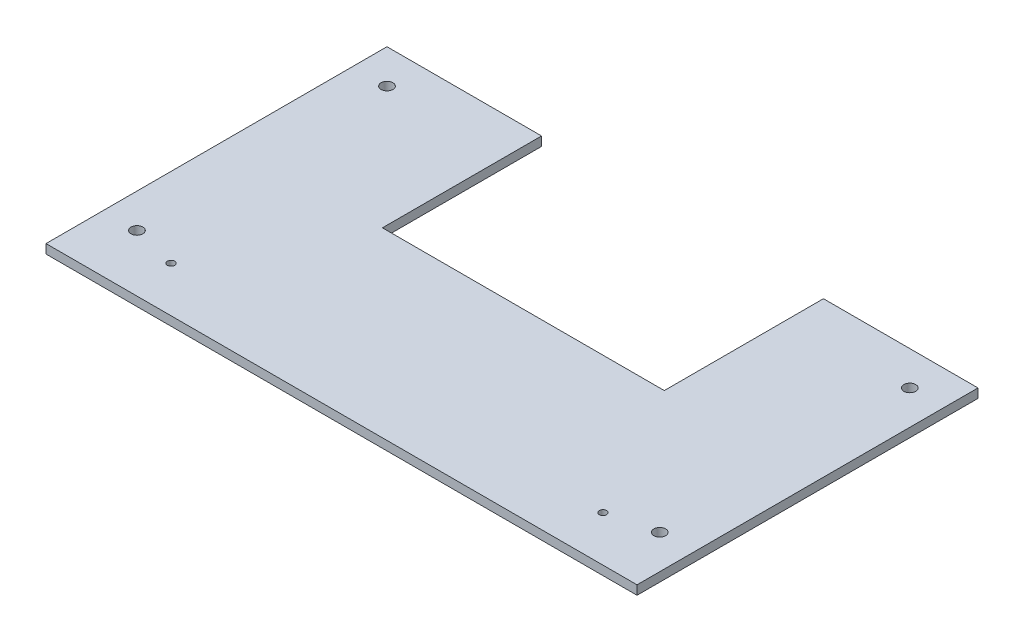
SolidWorks part; units mm, degrees
ref_plane "Alzado" through (0, 0, 0) normal (0, 0, 1) x (1, 0, 0)
ref_plane "Planta" through (0, 0, 0) normal (0, 1, 0) x (1, 0, 0)
ref_plane "Vista lateral" through (0, 0, 0) normal (1, 0, 0) x (0, 0, -1)
sketch "Croquis1" plane through (0, 0, 0) normal (0, 1, 0) x (1, 0, 0)
  line L1 (-130, -75) -> (130, -75)
  line L2 (-130, -75) -> (-130, 75)
  line L3 (-130, 75) -> (130, 75)
  line L4 (130, -75) -> (130, 75)
  line L5 (-130, -75) -> (130, 75) construction
  line L6 (-130, 75) -> (130, -75) construction
  point P0 (0, 0)
  dimension "D1" = 260
  dimension "D2" = 150
extrude "Saliente-Extruir1" add sketch "Croquis1" along normal blind 4
sketch "Croquis2" plane through (0, 4, 0) normal (0, 1, 0) x (1, 0, 0)
  line L0 (130, 75) -> (-130, 75) construction
  line L1 (-62, 5) -> (62, 5)
  line L2 (-62, 5) -> (-62, 75)
  line L3 (-62, 75) -> (62, 75)
  line L4 (62, 5) -> (62, 75)
  line L5 (-130, 75) -> (-130, -75) construction
  circle A0 centre (-115, 60) radius 2.6
  circle A1 centre (115, 60) radius 2.6
  circle A2 centre (115, -50) radius 2.6
  circle A3 centre (-115, -50) radius 2.6
  dimension "D4" = 5.2
  dimension "D5" = 15
  dimension "D1" = 62
  dimension "D2" = 62
  dimension "D3" = 70
  dimension "D6" = 15
  dimension "D7" = 2
  dimension "D8" = 2
extrude "Cortar-Extruir1" cut sketch "Croquis2" against normal blind 4
sketch "Croquis3" plane through (0, 4, 0) normal (0, 1, 0) x (1, 0, 0)
  line L7 (130, -75) -> (130, 75) construction
  line L8 (-130, -75) -> (130, -75) construction
  circle A0 centre (95, -55) radius 1.6
  circle A1 centre (-95, -55) radius 1.6
  dimension "D4" = 3.2
  dimension "D1" = 35
  dimension "D2" = 20
  dimension "D8" = 190
  dimension "D7" = 2
extrude "Cortar-Extruir2" cut sketch "Croquis3" against normal blind 10
